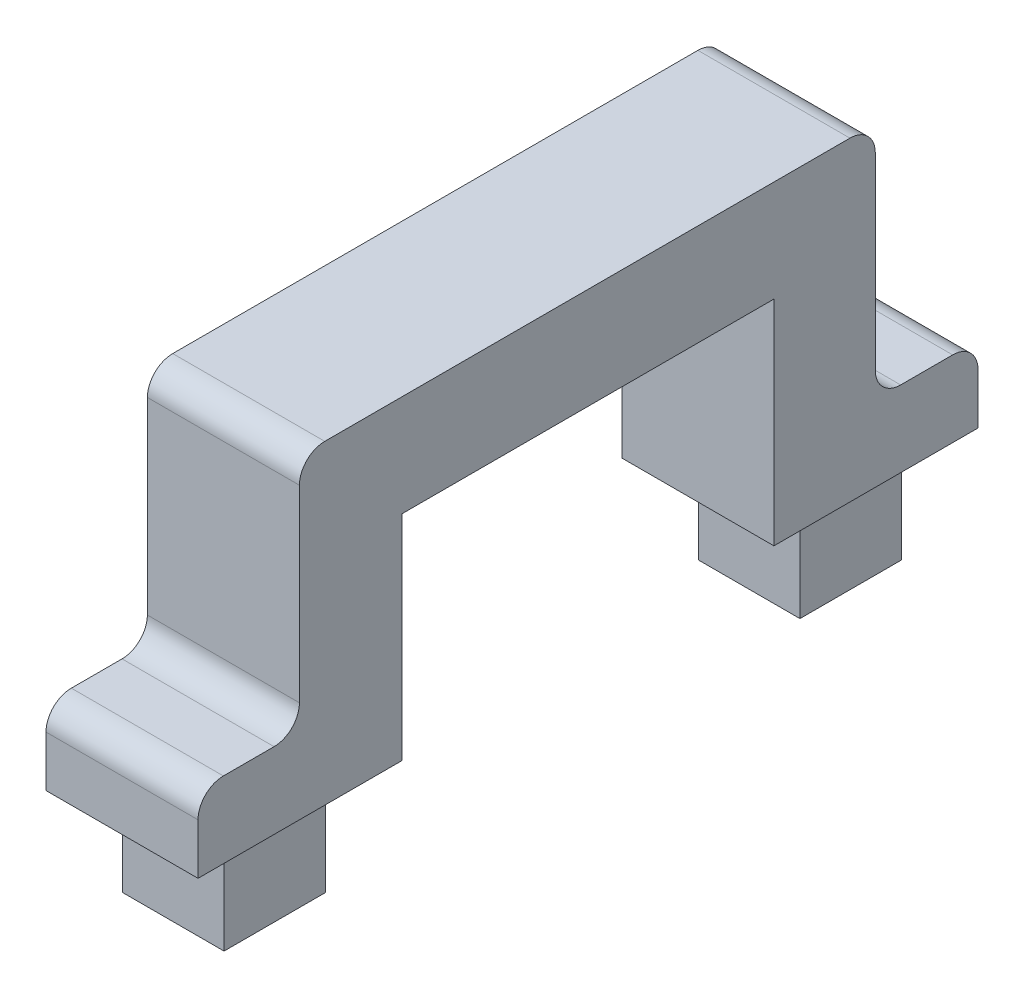
SolidWorks part; units mm, degrees
material "ABS"
ref_plane "Front Plane" through (0, 0, 0) normal (0, 0, 1) x (1, 0, 0)
ref_plane "Top Plane" through (0, 0, 0) normal (0, 1, 0) x (1, 0, 0)
ref_plane "Right Plane" through (0, 0, 0) normal (1, 0, 0) x (0, 0, -1)
sketch "Sketch1" plane through (0, 0, 0) normal (1, 0, 0) x (0, 0, -1)
  line L0 (0, 0) -> (12.7848, 0)
  line L1 (12.7848, 0) -> (12.7848, 13.3902)
  line L2 (12.7848, 13.3902) -> (36.0779, 13.3902)
  line L3 (36.0779, 13.3902) -> (36.0779, 0)
  line L5 (6.351, 19.7402) -> (41.4309, 19.7402)
  line L7 (48.8626, 0) -> (36.0779, 0)
  line L8 (6.351, 19.7402) -> (6.351, 4.7625)
  line L9 (6.351, 4.7625) -> (0, 4.7625)
  line L10 (0, 4.7625) -> (0, 0)
  line L11 (41.4309, 19.7402) -> (42.4279, 19.7402)
  line L12 (42.4279, 19.7402) -> (42.4279, 4.7625)
  line L13 (42.4279, 4.7625) -> (48.8626, 4.7625)
  line L14 (48.8626, 4.7625) -> (48.8626, 0)
  dimension "D1" = 6.35
  dimension "D2" = 12.7848
  dimension "D3" = 12.7848
  dimension "D4" = 0
  dimension "D5" = 13.3902
  dimension "D6" = 23.2931
  dimension "D7" = 35.0799
  dimension "D8" = 6.4338
  dimension "D9" = 4.7625
  dimension "D10" = 4.7625
  dimension "D11" = 6.35
extrude "Boss-Extrude1" add sketch "Sketch1" along normal blind 9.525
ref_plane "Plane2" through (0, 0, -24.4307) normal (0, 0, 1) x (1, 0, 0)
sketch "Sketch2" plane through (0, 4.7625, 0) normal (0, 1, 0) x (1, 0, 0)
  line L0 (0, 48.8626) -> (0, 42.4279) construction
  line L1 (9.525, 48.8626) -> (0, 48.8626) construction
  circle A0 centre (4.7625, 45.6876) radius 0.508
  circle A1 centre (4.7625, 3.1757) radius 0.7938
  dimension "D1" = 4.7625
  dimension "D3" = 42.512
  dimension "D4" = 1.016
  dimension "D2" = 3.175
extrude "Cut-Extrude1" [suppressed] cut sketch "Sketch2" against normal up to next
sketch "Sketch3" plane through (0, 0, 0) normal (-1, 0, 0) x (0, 0, 1)
  line L0 (-36.0779, 0) -> (-48.8626, 0) construction
  line L1 (-36.0779, 13.3902) -> (-36.0779, 0) construction
  circle A0 centre (-38.3232, 6.6853) radius 0.508
  circle A1 centre (-10.5229, 6.6951) radius 0.508
  dimension "D3" = 1.016
  dimension "D1" = 6.6853
  dimension "D2" = 2.2454
  dimension "D4" = 27.8003
extrude "Cut-Extrude2" cut sketch "Sketch3" against normal blind 6.35
fillet "Fillet1" radius 1.5875 6 edges at (4.7625, 4.7625, 0) (4.7625, 4.7625, -6.351) (4.7625, 19.7402, -6.351) (4.7625, 19.7402, -42.4279) (4.7625, 4.7625, -48.8626) (4.7625, 4.7625, -42.4279)
sketch "Esquisse1" plane through (0, 0, 0) normal (0, -1, 0) x (1, 0, 0)
  line L0 (0, -36.0779) -> (0, -48.8626) construction
  line L1 (1.5875, -45.6452) -> (7.9375, -45.6452)
  line L2 (1.5875, -45.6452) -> (1.5875, -39.2952)
  line L3 (1.5875, -39.2952) -> (7.9375, -39.2952)
  line L4 (7.9375, -45.6452) -> (7.9375, -39.2952)
  line L5 (9.525, -48.8626) -> (0, -48.8626) construction
  line L6 (0, -24.4313) -> (9.525, -24.4313) construction
  line L7 (0, -12.7848) -> (0, -36.0779) construction
  line L8 (9.525, -12.7848) -> (9.525, -36.0779) construction
  line L9 (7.9375, -3.2174) -> (7.9375, -9.5674)
  line L10 (1.5875, -9.5674) -> (7.9375, -9.5674)
  line L11 (1.5875, -3.2174) -> (1.5875, -9.5674)
  line L12 (1.5875, -3.2174) -> (7.9375, -3.2174)
  point P6 (0, -42.4702)
  point P7 (1.5875, -42.4702)
  point P10 (4.7625, -48.8626)
  point P11 (4.7625, -45.6452)
  dimension "D1" = 6.35
extrude "Boss.-Extru.1" add sketch "Esquisse1" along normal blind 6.35
